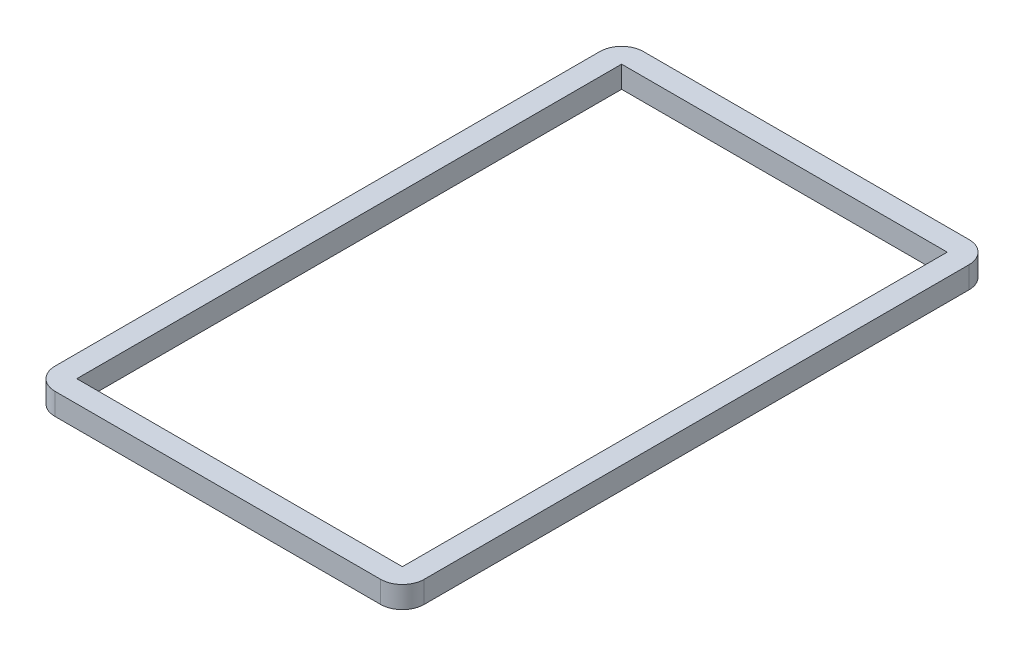
SolidWorks part; units mm, degrees
ref_plane "Front Plane" through (0, 0, 0) normal (0, 0, 1) x (1, 0, 0)
ref_plane "Top Plane" through (0, 0, 0) normal (0, 1, 0) x (1, 0, 0)
ref_plane "Right Plane" through (0, 0, 0) normal (1, 0, 0) x (0, 0, -1)
sketch "Sketch1" plane through (0, 0, 0) normal (0, 1, 0) x (1, 0, 0)
  line L0 (-25.4, -40.4812) -> (25.4, 40.4812) construction
  line L1 (-22.4, -40.4812) -> (22.4, -40.4812)
  line L2 (-25.4, -37.4812) -> (-25.4, 37.4812)
  line L3 (-22.4, 40.4812) -> (22.4, 40.4812)
  line L4 (25.4, -37.4812) -> (25.4, 37.4812)
  line L5 (-22.4, -37.4812) -> (22.4, -37.4812)
  line L6 (22.4, -37.4812) -> (22.4, 37.4812)
  line L7 (-22.4, 37.4812) -> (22.4, 37.4812)
  line L8 (-22.4, -37.4812) -> (-22.4, 37.4812)
  arc A0 (22.4, 40.4812) -> (25.4, 37.4812) centre (22.4, 37.4812) cw
  arc A1 (25.4, -37.4812) -> (22.4, -40.4812) centre (22.4, -37.4812) cw
  arc A2 (-22.4, -40.4812) -> (-25.4, -37.4812) centre (-22.4, -37.4812) cw
  arc A3 (-25.4, 37.4812) -> (-22.4, 40.4812) centre (-22.4, 37.4812) cw
  arc A4 (22.4, -37.4812) -> (22.4, -37.4812) centre (22.4, -37.4812) cw
  arc A5 (22.4, 37.4812) -> (22.4, 37.4812) centre (22.4, 37.4812) cw
  arc A6 (-22.4, 37.4812) -> (-22.4, 37.4812) centre (-22.4, 37.4812) cw
  arc A7 (-22.4, -37.4812) -> (-22.4, -37.4812) centre (-22.4, -37.4812) cw
  point P4 (0, 0)
  point P16 (-25.4, 40.4812)
  point P17 (0, 0)
  dimension "D3" = 3
  dimension "D1" = 50.8
  dimension "D2" = 80.9625
  dimension "D4" = 3
extrude "Boss-Extrude1" add sketch "Sketch1" along normal blind 3
